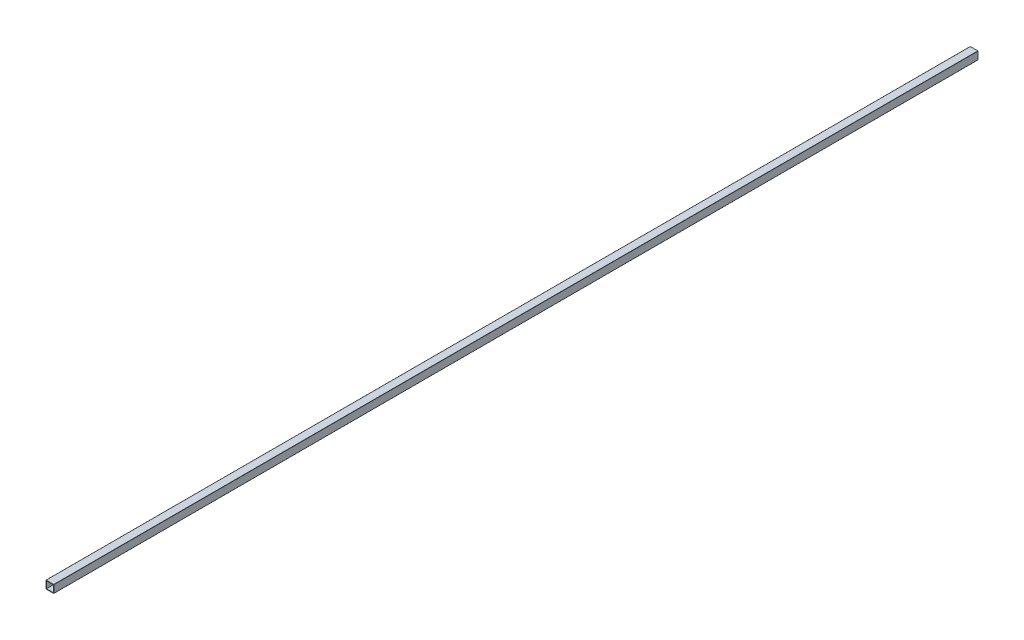
SolidWorks part; units mm, degrees
material "AISI 1035 Acero (SS)"
ref_plane "Alzado" through (0, 0, 0) normal (0, 0, 1) x (1, 0, 0)
ref_plane "Planta" through (0, 0, 0) normal (0, 1, 0) x (1, 0, 0)
ref_plane "Vista lateral" through (0, 0, 0) normal (1, 0, 0) x (0, 0, -1)
sketch "Croquis1" plane through (0, 0, 0) normal (0, 0, 1) x (1, 0, 0)
  line L0 (-22.36, -22.36) -> (-22.36, 22.36)
  line L1 (-24.4, -25.4) -> (24.4, -25.4)
  line L2 (-25.4, -24.4) -> (-25.4, 24.4)
  line L3 (-24.4, 25.4) -> (24.4, 25.4)
  line L4 (25.4, -24.4) -> (25.4, 24.4)
  line L5 (-25.4, -25.4) -> (25.4, 25.4) construction
  line L6 (-25.4, 25.4) -> (25.4, -25.4) construction
  line L7 (-22.36, 22.36) -> (22.36, 22.36)
  line L8 (22.36, -22.36) -> (22.36, 22.36)
  line L9 (-22.36, -22.36) -> (22.36, -22.36)
  line L10 (-25.4, 25.4) -> (25.4, 25.4) construction
  line L11 (25.4, -25.4) -> (25.4, 25.4) construction
  line L12 (-25.4, -25.4) -> (25.4, -25.4) construction
  line L13 (-25.4, -25.4) -> (-25.4, 25.4) construction
  arc A0 (24.4, 25.4) -> (25.4, 24.4) centre (24.4, 24.4) cw
  arc A1 (24.4, -25.4) -> (25.4, -24.4) centre (24.4, -24.4) ccw
  arc A2 (-24.4, -25.4) -> (-25.4, -24.4) centre (-24.4, -24.4) cw
  arc A3 (-25.4, 24.4) -> (-24.4, 25.4) centre (-24.4, 24.4) cw
  point P0 (0, 0)
  dimension "D2" = 1
  dimension "D1" = 50.8
  dimension "D3" = 3.04
extrude "Saliente-Extruir1" add sketch "Croquis1" along normal blind 6000
